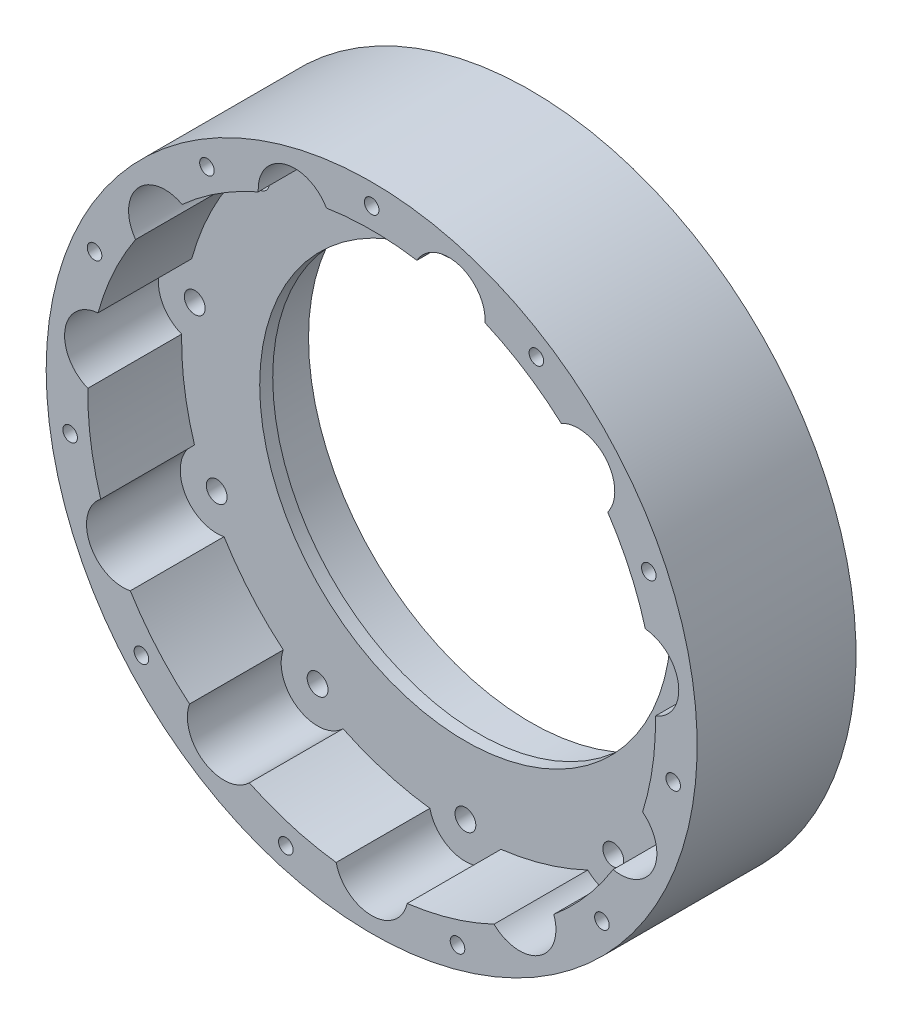
SolidWorks part; units mm, degrees
ref_plane "前视基准面" through (0, 0, 0) normal (0, 0, 1) x (1, 0, 0)
ref_plane "上视基准面" through (0, 0, 0) normal (0, 1, 0) x (1, 0, 0)
ref_plane "右视基准面" through (0, 0, 0) normal (1, 0, 0) x (0, 0, -1)
sketch "草图1" plane through (0, 0, 0) normal (0, 0, 1) x (1, 0, 0)
  line L0 (-14.791, 50.3734) -> (-39.6769, 34.3802) construction
  line L1 (-27.2339, 42.3768) -> (-40.8412, 63.5501) construction
  circle A0 centre (0, 0) radius 39.5
  circle A1 centre (0, 0) radius 62.5
  circle A2 centre (0, 0) radius 52.5 construction
  circle A3 centre (0, -52.5) radius 2
  circle A4 centre (-28.3836, -44.1658) radius 2
  circle A5 centre (-47.7557, -21.8093) radius 2
  circle A6 centre (-51.9656, 7.4715) radius 2
  circle A7 centre (-39.6769, 34.3802) radius 2
  circle A8 centre (-14.791, 50.3734) radius 2
  circle A9 centre (14.791, 50.3734) radius 2
  circle A10 centre (39.6769, 34.3802) radius 2
  circle A11 centre (51.9656, 7.4715) radius 2
  circle A12 centre (47.7557, -21.8093) radius 2
  circle A13 centre (28.3836, -44.1658) radius 2
  circle A14 centre (0, 0) radius 58.5 construction
  circle A15 centre (-31.626, 49.211) radius 1.4
  circle A16 centre (0, 58.4972) radius 1.4
  circle A17 centre (31.626, 49.211) radius 1.4
  circle A18 centre (53.2109, 24.3006) radius 1.4
  circle A19 centre (57.9018, -8.325) radius 1.4
  circle A20 centre (44.2092, -38.3075) radius 1.4
  circle A21 centre (16.4806, -56.1277) radius 1.4
  circle A22 centre (-16.4806, -56.1277) radius 1.4
  circle A23 centre (-44.2092, -38.3075) radius 1.4
  circle A24 centre (-57.9018, -8.325) radius 1.4
  circle A25 centre (-53.2109, 24.3006) radius 1.4
  dimension "D1" = 79
  dimension "D2" = 125
  dimension "D3" = 105
  dimension "D4" = 4
  dimension "D6" = 117
  dimension "D7" = 2.8
  dimension "D5" = 11
  dimension "D8" = 11
extrude "凸台-拉伸1" add sketch "草图1" along normal blind 30.5 contours A1
sketch "草图2" plane through (0, 0, 30.5) normal (0, 0, 1) x (1, 0, 0)
  circle A0 centre (0, 0) radius 54.5
  dimension "D1" = 109
extrude "切除-拉伸1" cut sketch "草图2" against normal blind 18 contours A0
sketch "草图3" plane through (0, 0, 30.5) normal (0, 0, 1) x (1, 0, 0)
  circle A1 centre (-39.6769, 34.3802) radius 7
  circle A2 centre (-14.791, 50.3734) radius 7
  circle A3 centre (14.791, 50.3734) radius 7
  circle A4 centre (39.6769, 34.3802) radius 7
  circle A5 centre (51.9656, 7.4715) radius 7
  circle A6 centre (47.7557, -21.8093) radius 7
  circle A7 centre (28.3836, -44.1658) radius 7
  circle A8 centre (0, -52.5) radius 7
  circle A9 centre (-28.3836, -44.1658) radius 7
  circle A10 centre (-47.7557, -21.8093) radius 7
  circle A11 centre (-51.9656, 7.4715) radius 7
  dimension "D1" = 14
  dimension "D2" = 11
extrude "切除-拉伸2" cut sketch "草图3" against normal blind 18
sketch "草图4" plane through (0, 0, 0) normal (0, 0, -1) x (-1, 0, 0)
  circle A0 centre (0, 0) radius 42.625
  point P3 (0, 0)
  dimension "D1" = 85.25
extrude "切除-拉伸3" cut sketch "草图4" against normal blind 10
